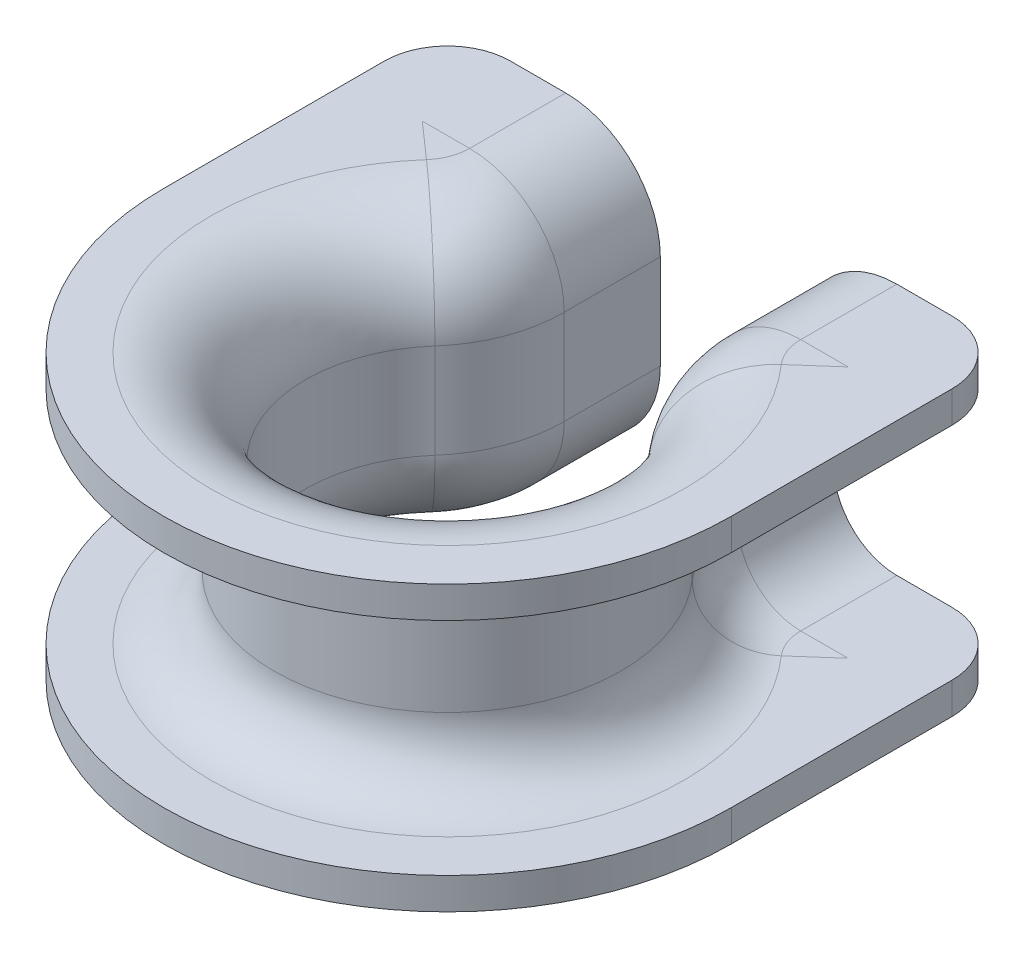
SolidWorks part; units mm, degrees
material "Polyetheretherketone (PEEK)"
ref_plane "Front Plane" through (0, 0, 0) normal (0, 0, 1) x (1, 0, 0)
ref_plane "Top Plane" through (0, 0, 0) normal (0, 1, 0) x (1, 0, 0)
ref_plane "Right Plane" through (0, 0, 0) normal (1, 0, 0) x (0, 0, -1)
sketch "Sketch6" plane through (0, 0, 0) normal (0, 1, 0) x (1, 0, 0)
  line L0 (-4.5, 18) -> (-4.5, 11.9059)
  line L1 (0, -9) -> (0, 59.3523) construction
  line L2 (4.5, 18) -> (4.5, 11.9059)
  arc A0 (-4.5, 11.9059) -> (-6.75, 5.9529) centre (-13.5, 11.9059) cw
  arc A1 (-6.75, 5.9529) -> (6.75, 5.9529) centre (0, 0) ccw
  arc A2 (4.5, 11.9059) -> (6.75, 5.9529) centre (13.5, 11.9059) ccw
  dimension "D2" = 9
  dimension "D4" = 9
  dimension "D1" = 9
  dimension "D3" = 18
sketch "Sketch3" plane through (0, 0, 0) normal (1, 0, 0) x (0, 0, -1)
  line L5 (-9, -3) -> (-9, 3)
  line L6 (0, -6) -> (0, 8.4312) construction
  line L7 (-9, 0) -> (0, 0) construction
  line L8 (-15, 9) -> (-18, 9)
  line L10 (-15, -9) -> (-18, -9)
  line L11 (-15, -7) -> (-18, -7)
  line L12 (-11, -3) -> (-11, 3)
  line L13 (-15, 7) -> (-18, 7)
  line L14 (-18, 7) -> (-18, 9)
  line L15 (-18, -7) -> (-18, -9)
  arc A1 (-9, 3) -> (-15, 9) centre (-15, 3) ccw
  arc A2 (-9, -3) -> (-15, -9) centre (-15, -3) cw
  arc A3 (-11, -3) -> (-15, -7) centre (-15, -3) cw
  arc A4 (-11, 3) -> (-15, 7) centre (-15, 3) ccw
  dimension "D1" = 18
  dimension "D3" = 6
  dimension "D2" = 3
  dimension "D4" = 2
sweep "Sweep1" add profiles "Sketch3" path "Sketch6"
sketch "Sketch7" plane through (0, 0, -18) normal (0, 0, -1) x (-1, 0, 0)
  line L1 (13.5, -7) -> (18, -7)
  line L2 (13.5, -7) -> (13.5, -9)
  line L3 (13.5, -9) -> (18, -9)
  line L4 (18, -7) -> (18, -9)
  line L5 (13.5, 7) -> (18, 7)
  line L6 (13.5, 7) -> (13.5, 9)
  line L7 (13.5, 9) -> (18, 9)
  line L8 (18, 7) -> (18, 9)
  line L9 (-13.5, 9) -> (-18, 9)
  line L10 (-13.5, 9) -> (-13.5, 7)
  line L11 (-13.5, 7) -> (-18, 7)
  line L12 (-18, 9) -> (-18, 7)
  line L13 (-13.5, -7) -> (-18, -7)
  line L14 (-13.5, -7) -> (-13.5, -9)
  line L15 (-13.5, -9) -> (-18, -9)
  line L16 (-18, -7) -> (-18, -9)
extrude "Boss-Extrude1" add sketch "Sketch7" against normal up to surface (18 mm away)
fillet "Fillet1" radius 4 4 edges at (18, -8, -18) (18, 8, -18) (-18, 8, -18) (-18, -8, -18)
